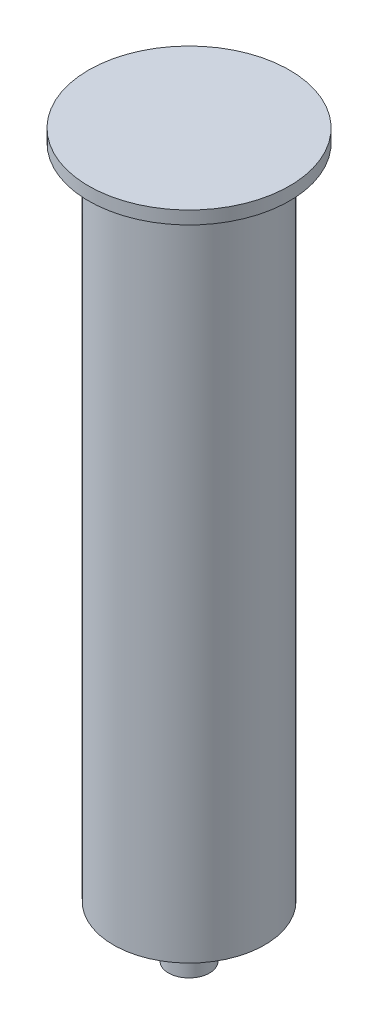
SolidWorks part; units mm, degrees
ref_plane "Płaszczyzna przednia" through (0, 0, 0) normal (0, 0, 1) x (1, 0, 0)
ref_plane "Płaszczyzna górna" through (0, 0, 0) normal (0, 1, 0) x (1, 0, 0)
ref_plane "Płaszczyzna prawa" through (0, 0, 0) normal (1, 0, 0) x (0, 0, -1)
sketch "Szkic1" plane through (0, 0, 0) normal (0, 0, 1) x (1, 0, 0)
  line L0 (0, 0) -> (0, -167) construction
  line L1 (0, 0) -> (-23.25, 0)
  line L2 (-23.25, 0) -> (-23.25, -3)
  line L3 (-23.25, -3) -> (-17.5, -3)
  line L4 (-17.5, -3) -> (-17.5, -155)
  line L5 (-17.5, -155) -> (-4.75, -160)
  line L6 (-4.75, -160) -> (-4.75, -167)
  line L7 (-4.75, -167) -> (0, -167)
  line L8 (0, 0) -> (0, -167)
  dimension "D1" = 46.5
  dimension "D2" = 35
  dimension "D3" = 3
  dimension "D4" = 155
  dimension "D5" = 7
  dimension "D6" = 12
  dimension "D7" = 9.5
revolve "Obrót1" add sketch "Szkic1" angle 360 about L0
